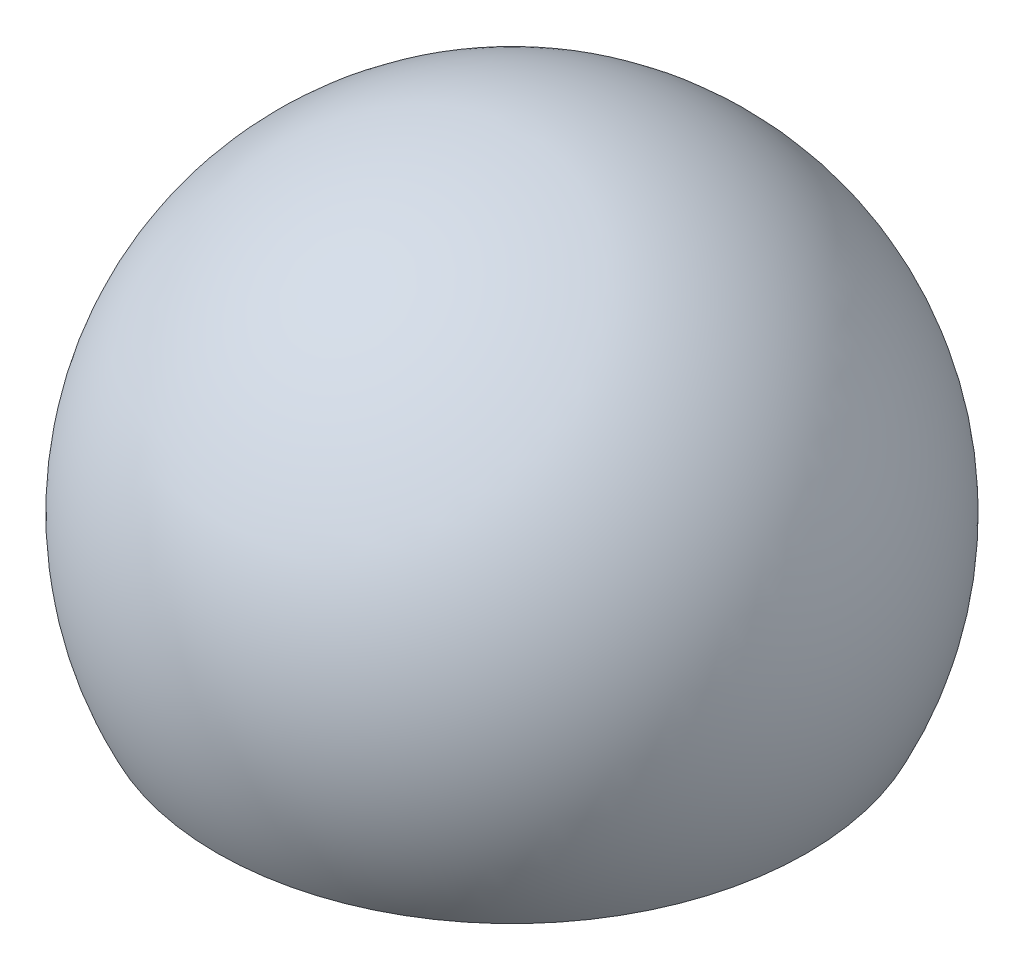
SolidWorks part; units mm, degrees
ref_plane "Front Plane" through (0, 0, 0) normal (0, 0, 1) x (1, 0, 0)
ref_plane "Top Plane" through (0, 0, 0) normal (0, 1, 0) x (1, 0, 0)
ref_plane "Right Plane" through (0, 0, 0) normal (1, 0, 0) x (0, 0, -1)
sketch "Sketch1" plane through (0, 0, 0) normal (0, 0, 1) x (1, 0, 0)
  line L0 (-8, 0) -> (0, 0)
  line L1 (0, 0) -> (0, 4) construction
  line L2 (0, 0) -> (0, 12.9443)
  line L3 (-4, 0) -> (0, 0) construction
  line L4 (-4, 0) -> (-4, 8) construction
  line L5 (-4, 8) -> (0, 8) construction
  arc A0 (0, 12.9443) -> (-8, 0) centre (0, 4) ccw
  point P4 (0, 0)
  dimension "D1" = 8.9443
  dimension "D2" = 8
  dimension "D4" = 4
  dimension "D5" = 4
revolve "Revolve1" add sketch "Sketch1" angle 360 about L2
sketch "Sketch2" plane through (0, 0, 0) normal (0, -1, 0) x (1, 0, 0)
  line L1 (-4, -4) -> (4, -4)
  line L2 (-4, -4) -> (-4, 4)
  line L3 (-4, 4) -> (4, 4)
  line L4 (4, -4) -> (4, 4)
  dimension "D1" = 4
  dimension "D2" = 4
  dimension "D3" = 8
  dimension "D4" = 8
extrude "Cut-Extrude1" cut sketch "Sketch2" against normal blind 8
